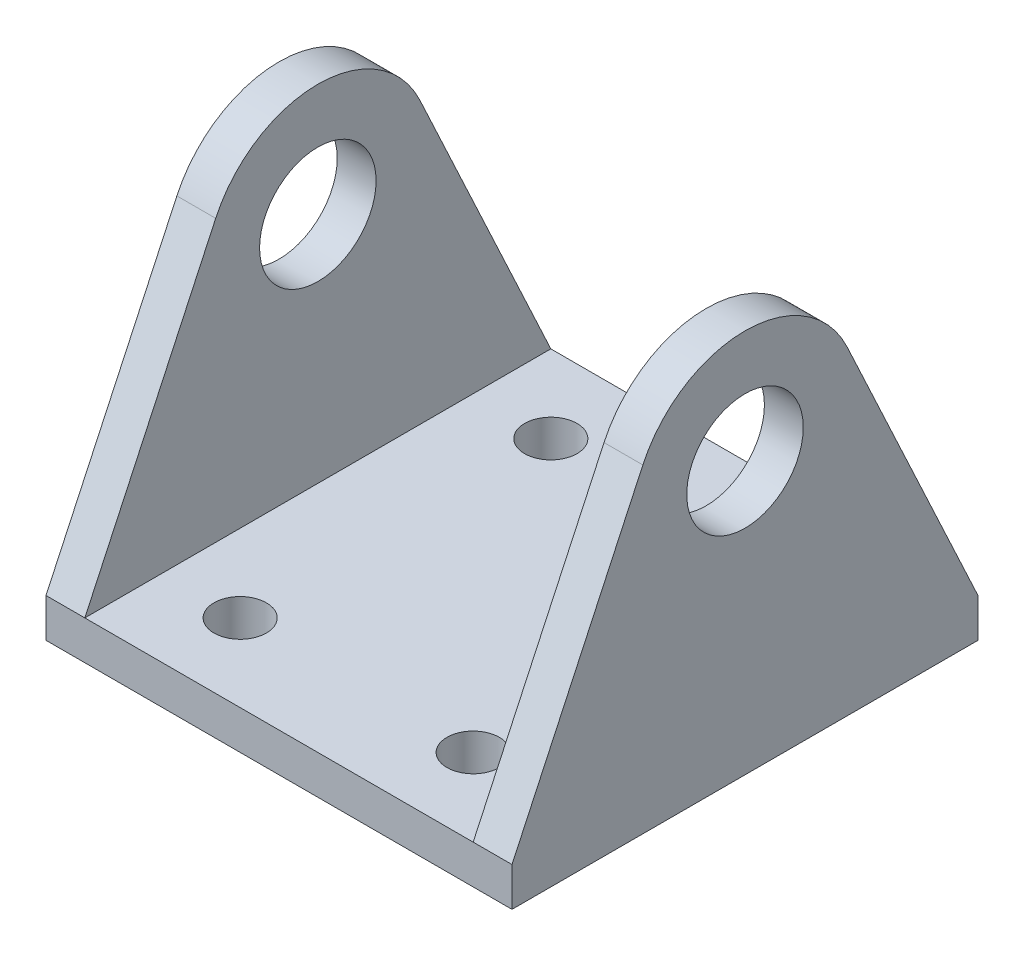
SolidWorks part; units mm, degrees
ref_plane "Plan de face" through (0, 0, 0) normal (0, 0, 1) x (1, 0, 0)
ref_plane "Plan de dessus" through (0, 0, 0) normal (0, 1, 0) x (1, 0, 0)
ref_plane "Plan de droite" through (0, 0, 0) normal (1, 0, 0) x (0, 0, -1)
sketch "Esquisse1" plane through (0, 0, 0) normal (0, 1, 0) x (1, 0, 0)
  line L1 (0, 0) -> (120, 0)
  line L2 (0, 0) -> (0, 120)
  line L3 (0, 120) -> (120, 120)
  line L4 (120, 0) -> (120, 120)
  dimension "D1" = 120
  dimension "D2" = 120
extrude "Boss.-Extru.2" add sketch "Esquisse1" along normal blind 10
sketch "Esquisse2" plane through (120, 0, 0) normal (1, 0, 0) x (0, 0, -1)
  line L0 (60, 0) -> (60, 138.6704) construction
  line L1 (0, 0) -> (120, 0) construction
  line L2 (60, 138.6704) -> (120, 10) construction
  line L3 (120, 10) -> (0, 10) construction
  line L4 (0, 10) -> (60, 138.6704) construction
  line L5 (92.0215, 70) -> (60, 70) construction
  line L6 (60, 70) -> (27.9785, 70) construction
  line L7 (86.3023, 82.265) -> (120, 10)
  line L8 (120, 10) -> (0, 10)
  line L9 (0, 10) -> (33.6977, 82.265)
  circle A0 centre (60, 70) radius 15
  arc A1 (86.3023, 82.265) -> (33.6977, 82.265) centre (60, 70) ccw
  dimension "D1" = 30
  dimension "D2" = 60
  dimension "D3" = 65
extrude "Boss.-Extru.3" add sketch "Esquisse2" against normal up to surface (120 mm away) up to face at (0, 5, -60)
sketch "Esquisse3" plane through (0, 0, 0) normal (0, 0, 1) x (1, 0, 0)
  line L0 (0, 10) -> (120, 10) construction
  line L1 (10, 10) -> (110, 10)
  line L2 (10, 10) -> (10, 132.4018)
  line L3 (10, 132.4018) -> (110, 132.4018)
  line L4 (110, 10) -> (110, 132.4018)
  line L5 (0, 10) -> (0, 82.265) construction
  line L6 (120, 82.265) -> (120, 10) construction
  dimension "D1" = 10
  dimension "D2" = 10
extrude "Enlèv. mat.-Extru.1" cut sketch "Esquisse3" against normal through all
sketch "Esquisse4" plane through (0, 10, 0) normal (0, 1, 0) x (1, 0, 0)
  line L0 (30, 20) -> (30, 100) construction
  line L1 (10, 0) -> (110, 0) construction
  line L2 (10, 0) -> (10, 120) construction
  line L3 (10, 120) -> (110, 120) construction
  line L4 (110, 0) -> (110, 120) construction
  line L5 (30, 100) -> (90, 100) construction
  line L6 (90, 20) -> (90, 100) construction
  line L7 (30, 20) -> (90, 20) construction
  line L8 (90, 100) -> (30, 20) construction
  circle A0 centre (30, 20) radius 6.75
  circle A1 centre (30, 100) radius 6.75
  circle A2 centre (90, 100) radius 6.75
  circle A3 centre (90, 20) radius 6.75
  dimension "D2" = 13.5
  dimension "D3" = 13.5
  dimension "D4" = 13.5
  dimension "D5" = 13.5
  dimension "D1" = 20
extrude "Enlèv. mat.-Extru.2" cut sketch "Esquisse4" against normal blind 10
